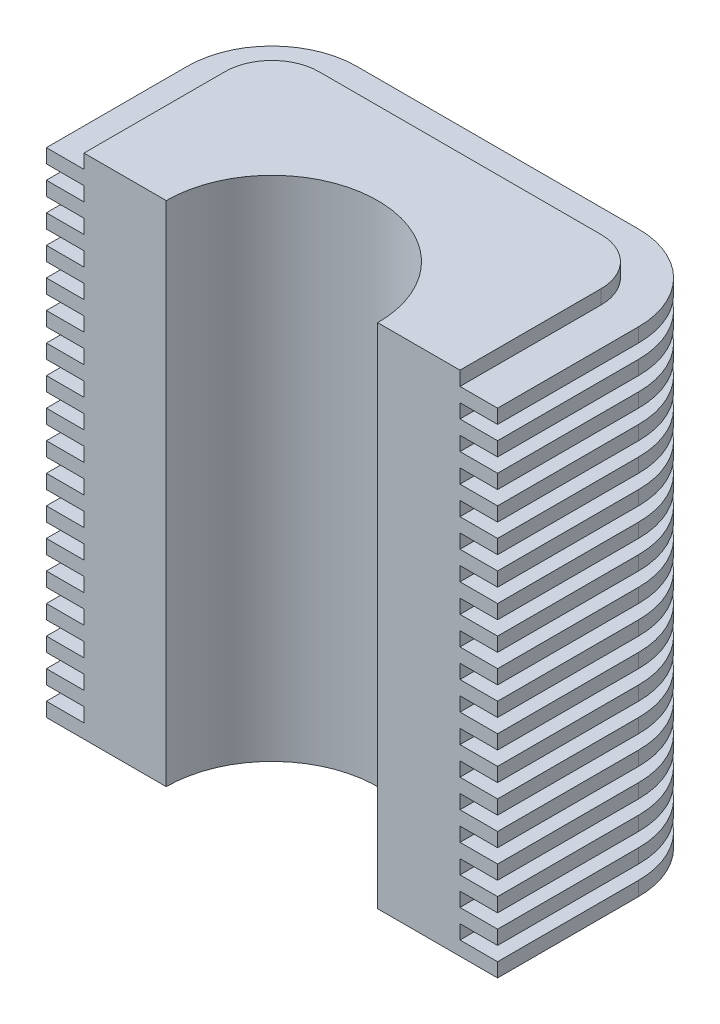
SolidWorks part; units mm, degrees
ref_plane "Płaszczyzna przednia" through (0, 0, 0) normal (0, 0, 1) x (1, 0, 0)
ref_plane "Płaszczyzna górna" through (0, 0, 0) normal (0, 1, 0) x (1, 0, 0)
ref_plane "Płaszczyzna prawa" through (0, 0, 0) normal (1, 0, 0) x (0, 0, -1)
sketch "Szkic1" plane through (0, 0, 0) normal (0, 1, 0) x (1, 0, 0)
  line L0 (-22.5, 0) -> (-40, 0)
  line L1 (-40, 0) -> (-40, 40)
  line L2 (-40, 40) -> (40, 40)
  line L3 (40, 40) -> (40, 0)
  line L4 (40, 0) -> (22.5, 0)
  arc A0 (-22.5, 0) -> (22.5, 0) centre (0, 0) cw
  point P4 (0, 0)
  point P9 (0, 0)
  point P10 (0, 0)
  dimension "D1" = 22.5
  dimension "D2" = 80
  dimension "D3" = 40
  dimension "D4" = 17.5
  dimension "D5" = 17.5
extrude "Dodanie-wyciągnięcie1" add sketch "Szkic1" along normal blind 108
fillet "Zaokrąglenie4" radius 10 2 edges at (40, 54, -40) (-40, 54, -40)
sketch "Szkic3" plane through (0, 0, 0) normal (0, 1, 0) x (1, 0, 0)
  line L0 (-40, 0) -> (-48, 0)
  line L10 (40, 0) -> (48, 0)
  line L13 (48, 0) -> (48, 30)
  line L14 (30, 48) -> (-30, 48)
  line L15 (-48, 30) -> (-48, 0)
  line L16 (48, 0) -> (48, 30)
  line L17 (30, 48) -> (-30, 48)
  line L18 (-48, 30) -> (-48, 0)
  line L22 (40, 0) -> (40, 30)
  line L23 (30, 40) -> (-30, 40)
  line L24 (-40, 30) -> (-40, 0)
  line L25 (-40, 0) -> (-22.5, 0)
  line L26 (22.5, 0) -> (40, 0)
  line L30 (-40, 0) -> (-22.5, 0)
  line L31 (22.5, 0) -> (40, 0)
  arc A8 (48, 30) -> (30, 48) centre (30, 30) ccw
  arc A9 (-30, 48) -> (-48, 30) centre (-30, 30) ccw
  arc A10 (48, 30) -> (30, 48) centre (30, 30) ccw
  arc A11 (-30, 48) -> (-48, 30) centre (-30, 30) ccw
  arc A13 (40, 30) -> (30, 40) centre (30, 30) ccw
  arc A14 (-30, 40) -> (-40, 30) centre (-30, 30) ccw
  arc A15 (22.5, 0) -> (-22.5, 0) centre (0, 0) ccw
  arc A18 (22.5, 0) -> (-22.5, 0) centre (0, 0) ccw
  dimension "D1" = 8
  dimension "D2" = 0
extrude "Dodanie-wyciągnięcie3" add sketch "Szkic3" along normal blind 3 contours L16 A10 L17 A11 L18 L0 L30 A18 L31 L10
pattern_linear "Szyk liniowy1" count 18 spacing 6 along (0, 1, 0) of "Dodanie-wyciągnięcie3"
